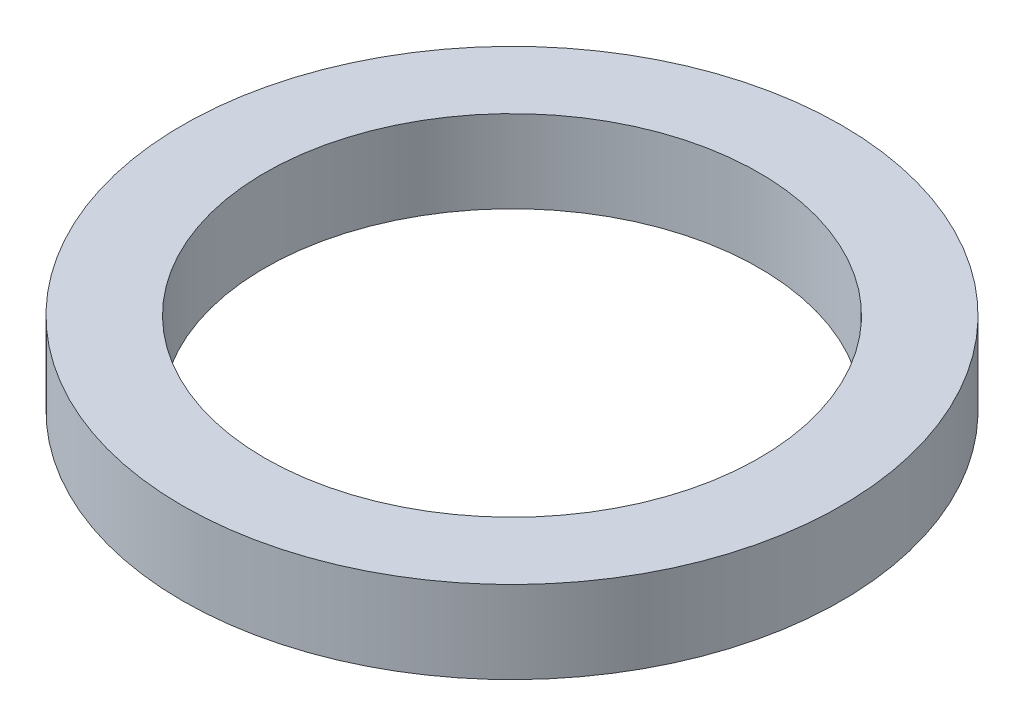
SolidWorks part; units mm, degrees
ref_plane "Front Plane" through (0, 0, 0) normal (0, 0, 1) x (1, 0, 0)
ref_plane "Top Plane" through (0, 0, 0) normal (0, 1, 0) x (1, 0, 0)
ref_plane "Right Plane" through (0, 0, 0) normal (1, 0, 0) x (0, 0, -1)
sketch "Sketch1" plane through (0, 0, 0) normal (0, 1, 0) x (1, 0, 0)
  circle A0 centre (0, 0) radius 12.7
  circle A1 centre (0, 0) radius 9.525
  dimension "D1" = 25.4
  dimension "D2" = 19.05
extrude "Boss-Extrude1" add sketch "Sketch1" along normal blind 3.175 contours A1 | A0
